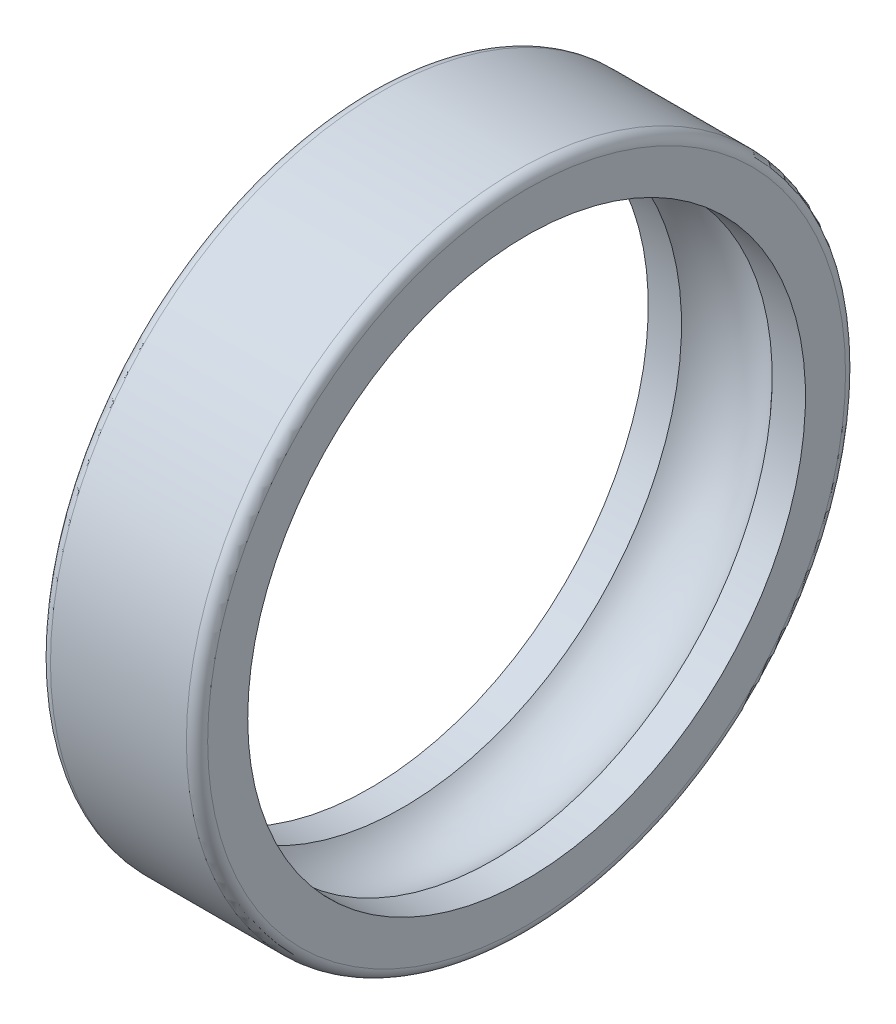
SolidWorks part; units mm, degrees
ref_plane "Front Plane" through (0, 0, 0) normal (0, 0, 1) x (1, 0, 0)
ref_plane "Top Plane" through (0, 0, 0) normal (0, 1, 0) x (1, 0, 0)
ref_plane "Right Plane" through (0, 0, 0) normal (1, 0, 0) x (0, 0, -1)
sketch "Sketch1" plane through (0, 0, 0) normal (0, 0, 1) x (1, 0, 0)
  line L0 (0, 0) -> (0, 123.5659) construction
  line L1 (0, 0) -> (66.8561, 0) construction
  line L2 (-15.5, 65) -> (15.5, 65)
  line L3 (-15.5, 65) -> (-15.5, 55)
  line L4 (-15.5, 55) -> (-8.9443, 55)
  line L5 (15.5, 65) -> (15.5, 55)
  line L6 (8.9443, 55) -> (15.5, 55)
  arc A0 (8.9443, 55) -> (-8.9443, 55) centre (0, 47) ccw
  dimension "D3" = 12
  dimension "D1" = 65
  dimension "D2" = 55
  dimension "D4" = 8
revolve "Revolve1" add sketch "Sketch1" angle 360 about L1
fillet "Fillet1" radius 2.1 2 edges at (15.5, 0, 65) (-15.5, 0, 65)
